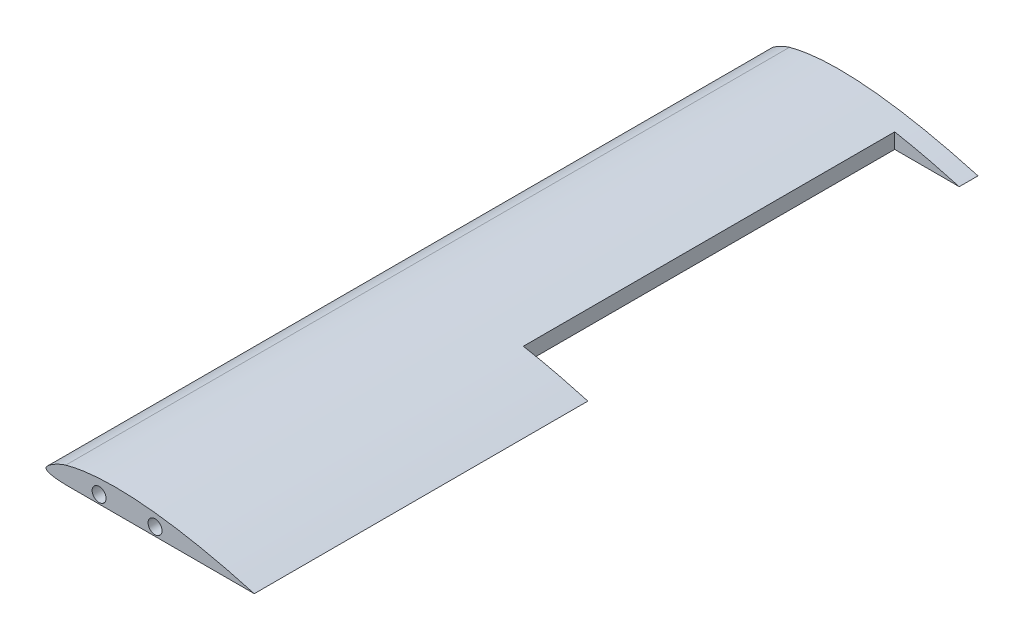
SolidWorks part; units mm, degrees
ref_plane "Спереди" through (0, 0, 0) normal (0, 0, 1) x (1, 0, 0)
ref_plane "Сверху" through (0, 0, 0) normal (0, 1, 0) x (1, 0, 0)
ref_plane "Справа" through (0, 0, 0) normal (1, 0, 0) x (0, 0, -1)
ref_plane "Плоскость4"
sketch "Эскиз1" plane through (0, 0, 0) normal (0, 0, 1) x (1, 0, 0)
  line L0 (17.2168, 0) -> (24.1571, 0)
  line L1 (24.1571, 0) -> (150, 0)
  arc A0 (14.5075, 0) -> (17.2168, 0) centre (15.8621, 58.4021) ccw
  spline S0 degree 3 poles (150, 0) (149.8103, 0.0535) (148.8822, 0.315) (147.2148, 0.7812) (144.639, 1.4911) (142.8004, 1.9884) (141.3183, 2.3846) (139.4528, 2.8811) (136.6768, 3.6046) (134.2803, 4.2119) (132.7921, 4.5848) (129.2358, 5.4697) (123.6524, 6.7978) (118.6331, 7.91) (115.6332, 8.5543) (112.827, 9.1477) (110.0153, 9.7153) (107.0035, 10.3033) (104.1852, 10.8417) (101.3616, 11.3518) (98.3391, 11.8786) (93.9391, 12.6222) (88.2743, 13.4797) (83.9782, 14.0488) (80.9402, 14.4335) (78.0977, 14.7702) (75.2508, 15.0677) (72.2039, 15.3694) (69.352, 15.6229) (66.4958, 15.8315) (63.4387, 16.0393) (60.5777, 16.1977) (57.7092, 16.3039) (56.1747, 16.3538) (54.7388, 16.3923) (53.3029, 16.4166) (51.7678, 16.4362) (50.3334, 16.4447) (48.901, 16.4378) (45.8405, 16.4119) (42.9833, 16.3304) (40.1345, 16.1761) (38.6139, 16.0899) (35.8528, 15.9017) (33.0174, 15.6301) (29.9988, 15.2873) (27.0919, 14.9079) (24.2789, 14.4406) (22.0363, 14.0235) (20.4413, 13.7077) (18.1073, 13.1883) (16.2535, 12.7297) (15.0549, 12.4095) (14.5965, 12.2828) (14.5075, 12.2582) knots 0 0 0 0 0.000556 0.002719 0.004883 0.008092 0.008092 0.00921 0.013537 0.016183 0.016183 0.017865 0.02652 0.032367 0.032367 0.035176 0.040459 0.040459 0.043831 0.04855 0.04855 0.052486 0.061142 0.064734 0.064734 0.069797 0.072826 0.072826 0.078453 0.080917 0.080917 0.087109 0.089009 0.089009 0.091436 0.093055 0.093055 0.095763 0.097101 0.097101 0.10441 0.105193 0.105193 0.10873 0.113048 0.113284 0.117362 0.121376 0.121376 0.123827 0.125981 0.128133 0.129209 0.129468 0.129468 0.129468 0.129468 weights 1 1 1 1 1 1 1 1 1 1 1 1 1 1 1 1 1 1 1 1 1 1 1 1 1 1 1 1 1 1 1 1 1 1 1 1 1 1 1 1 1 1 1 1 1 1 1 1 1 1 1 1 1 1 1
  spline S1 degree 3 poles (14.5075, 12.2582) (14.4875, 12.2539) (14.4469, 12.2452) (14.3857, 12.2317) (14.3033, 12.2124) (14.2007, 12.187) (14.0984, 12.1598) (14.0169, 12.1372) (13.9156, 12.1085) (13.8142, 12.0782) (13.6738, 12.0347) (13.5937, 12.0092) (13.4322, 11.9569) (13.1688, 11.8693) (12.8515, 11.758) (12.6365, 11.6794) (12.4766, 11.6204) (12.2124, 11.5211) (11.8995, 11.3986) (11.6912, 11.3151) (11.3758, 11.1877) (11.0662, 11.0589) (10.4923, 10.8126) (9.8722, 10.5382) (9.2664, 10.2556) (8.6563, 9.9625) (8.0494, 9.6632) (7.1849, 9.215) (6.2951, 8.728) (5.69, 8.3766) (5.1097, 8.0277) (4.8059, 7.839) (4.2552, 7.484) (3.961, 7.2872) (3.4181, 6.9072) (3.134, 6.6994) (2.867, 6.4926) (2.7317, 6.3876) (2.4714, 6.1801) (2.2146, 5.9616) (1.9568, 5.7332) (1.7055, 5.5015) (1.4693, 5.2619) (1.2404, 5.0151) (1.1297, 4.8881) (0.9692, 4.6876) (0.8658, 4.5525) (0.7667, 4.4091) (0.6734, 4.2643) (0.5863, 4.1187) (0.5127, 3.9696) (0.4782, 3.8903) (0.4444, 3.8119) (0.4121, 3.7248) (0.3665, 3.5662) (0.3494, 3.4827) (0.3409, 3.3966) (0.3364, 3.3454) (0.335, 3.2716) (0.3418, 3.1946) (0.3469, 3.1609) (0.3505, 3.1397) (0.3562, 3.1094) (0.3663, 3.0678) (0.3761, 3.0355) (0.3829, 3.0147) (0.3899, 2.9945) (0.3977, 2.9746) (0.4103, 2.9441) (0.4234, 2.9154) (0.4426, 2.8776) (0.468, 2.8312) (0.5076, 2.7683) (0.5452, 2.7172) (0.5718, 2.6831) (0.5983, 2.6499) (0.6262, 2.6176) (0.6554, 2.5856) (0.6845, 2.5542) (0.7146, 2.5239) (0.7456, 2.4939) (0.8075, 2.4351) (0.8726, 2.3799) (0.9405, 2.3266) (1.0079, 2.2745) (1.0774, 2.2253) (1.1488, 2.1774) (1.2903, 2.0836) (1.4366, 1.9991) (1.5883, 1.9193) (1.7385, 1.8412) (1.8924, 1.7693) (2.0503, 1.7009) (2.2063, 1.634) (2.3842, 1.564) (2.7066, 1.4462) (3.0273, 1.3387) (3.3557, 1.2415) (3.8219, 1.1116) (4.1806, 1.0234) (4.8168, 0.8827) (5.183, 0.8102) (5.8182, 0.6961) (6.1897, 0.636) (6.8222, 0.5426) (7.1992, 0.4922) (7.8288, 0.4155) (8.211, 0.3732) (9.1724, 0.2763) (9.9, 0.2167) (11.1959, 0.1293) (11.8686, 0.0933) (12.5509, 0.0637) (12.9578, 0.0464) (13.6317, 0.022) (14.2404, 0.0062) (14.5075, 0) knots -0.00005 -0.00005 -0.00005 -0.00005 0.00001 0.000072 0.000135 0.00026 0.000385 0.000447 0.00051 0.000696 0.000761 0.000945 0.000945 0.001263 0.001766 0.00194 0.00194 0.002271 0.002775 0.002936 0.002936 0.003783 0.003931 0.004792 0.0058 0.005921 0.006808 0.007817 0.008825 0.009834 0.009902 0.010842 0.010898 0.01185 0.011893 0.012859 0.012888 0.012888 0.013363 0.013867 0.013883 0.014381 0.014879 0.014879 0.015376 0.015376 0.015632 0.015874 0.015884 0.016136 0.016371 0.016371 0.016388 0.01662 0.01664 0.016869 0.016869 0.016892 0.017019 0.017082 0.017118 0.017118 0.017144 0.017207 0.017242 0.017242 0.017271 0.017304 0.017304 0.017367 0.017397 0.017429 0.017522 0.017615 0.017615 0.017649 0.01774 0.01774 0.017775 0.017864 0.017864 0.017901 0.018113 0.018113 0.018153 0.018362 0.018362 0.018405 0.01886 0.01886 0.018909 0.019357 0.019357 0.019414 0.019855 0.019918 0.020422 0.02085 0.020926 0.021845 0.021935 0.022841 0.022943 0.023836 0.023951 0.024831 0.02496 0.025826 0.025968 0.027817 0.027985 0.029807 0.029807 0.030002 0.03101 0.031798 0.031798 0.031798 0.031798 weights 1 1 1 1 1 1 1 1 1 1 1 1 1 1 1 1 1 1 1 1 1 1 1 1 1 1 1 1 1 1 1 1 1 1 1 1 1 1 1 1 1 1 1 1 1 1 1 1 1 1 1 1 1 1 1 1 1 1 1 1 1 1 1 1 1 1 1 1 1 1 1 1 1 1 1 1 1 1 1 1 1 1 1 1 1 1 1 1 1 1 1 1 1 1 1 1 1 1 1 1 1 1 1 1 1 1 1 1 1 1 1 1 1 1 1 1 1
extrude "Выдавливание1" add sketch "Эскиз1" along normal blind 520
ref_plane "Плоскость5"
sketch "Эскиз2" plane through (0, 0, 520) normal (0, 0, 1) x (1, 0, 0)
  circle A0 centre (78.7009, 6) radius 5
  circle A1 centre (38.5008, 6) radius 5
  dimension "D1" = 10
extrude "Выдавливание2" cut sketch "Эскиз2" against normal blind 200 contours A0 | A1
sketch "Эскиз3" plane through (0, 0, 0) normal (0, -1, 0) x (1, 0, 0)
  line L0 (128.3183, 305) -> (128.3183, 330)
  line L1 (128.3183, 330) -> (28.3183, 330)
  line L2 (28.3183, 330) -> (28.3183, 305)
  line L3 (28.3183, 305) -> (128.3183, 305)
  dimension "D1" = 25
  dimension "D2" = 100
extrude "Выдавливание3" add sketch "Эскиз3" along normal blind 35
sketch "Эскиз4" plane through (128.3183, 0, 0) normal (1, 0, 0) x (0, 0, -1)
  line L0 (-327.5, -25) -> (-327.5, -35)
  line L1 (-327.5, -35) -> (-307.5, -35)
  line L2 (-307.5, -35) -> (-307.5, -25)
  line L3 (-307.5, -25) -> (-307.5, -15)
  line L4 (-327.5, -15) -> (-327.5, -25)
  arc A0 (-307.5, -15) -> (-327.5, -15) centre (-317.5, -15) ccw
  dimension "D1" = 10
extrude "Выдавливание5" cut sketch "Эскиз4" against normal through all
sketch "Эскиз5" plane through (0, 0, 330) normal (0, 0, 1) x (1, 0, 0)
  circle A0 centre (98.3183, -25) radius 5
  circle A1 centre (78.3183, -25) radius 5
  circle A2 centre (58.3183, -25) radius 5
  line M1 (128.3183, 0) -> (28.3183, 0)
  line M2 (28.3183, 0) -> (28.3183, -35)
  line M3 (28.3183, -35) -> (128.3183, -35)
  line M4 (128.3183, -35) -> (128.3183, 0)
  dimension "D1" = 10
  dimension "D2" = 10
  dimension "D3" = 10
extrude "Выдавливание6" cut sketch "Эскиз5" against normal through all contours A2 A1 A0 M4 M1 M2 M3
sketch "Эскиз6" plane through (0, 0, 0) normal (0, -1, 0) x (1, 0, 0)
  line L0 (101.6272, 11.4767) -> (103.6272, 11.4767)
  line L1 (103.6272, 11.4767) -> (163.8005, 11.4767)
  line L2 (163.8005, 11.4767) -> (163.8005, 282.2938)
  line L3 (163.8005, 282.2938) -> (161.8005, 282.2938)
  line L4 (161.8005, 282.2938) -> (101.6272, 282.2938)
  line L5 (101.6272, 282.2938) -> (101.6272, 11.4767)
  line L6 (161.8005, 13.4767) -> (103.6272, 13.4767)
  line L7 (103.6272, 13.4767) -> (103.6272, 280.2938)
  line L8 (103.6272, 280.2938) -> (161.8005, 280.2938)
  line L9 (161.8005, 280.2938) -> (161.8005, 13.4767)
  line M2 (150, 0) -> (150, 520)
  dimension "D1" = 2
  dimension "D2" = 2
  dimension "D3" = 2
  dimension "D4" = 2
extrude "Выдавливание7" cut sketch "Эскиз6" against normal through all contours L8 L7 L6 M2
sketch "Эскиз7" plane through (0, 0, 0) normal (0, -1, 0) x (1, 0, 0)
  line L0 (103.6272, 25.8852) -> (103.6272, 27.8852)
  line L1 (103.6272, 27.8852) -> (101.6272, 27.8852)
  line L2 (101.6272, 27.8852) -> (101.6272, 25.8852)
  line L3 (101.6272, 25.8852) -> (103.6272, 25.8852)
  line L4 (103.6272, 45.8852) -> (103.6272, 47.8852)
  line L5 (103.6272, 47.8852) -> (101.6272, 47.8852)
  line L6 (101.6272, 47.8852) -> (101.6272, 45.8852)
  line L7 (101.6272, 45.8852) -> (103.6272, 45.8852)
  line L8 (103.6272, 35.8852) -> (103.6272, 37.8852)
  line L9 (103.6272, 37.8852) -> (101.6272, 37.8852)
  line L10 (101.6272, 37.8852) -> (101.6272, 35.8852)
  line L11 (101.6272, 35.8852) -> (103.6272, 35.8852)
  line L12 (103.6272, 55.8852) -> (103.6272, 57.8852)
  line L13 (103.6272, 57.8852) -> (101.6272, 57.8852)
  line L14 (101.6272, 57.8852) -> (101.6272, 55.8852)
  line L15 (101.6272, 55.8852) -> (103.6272, 55.8852)
  line L16 (103.6272, 65.8852) -> (103.6272, 67.8852)
  line L17 (103.6272, 67.8852) -> (101.6272, 67.8852)
  line L18 (101.6272, 67.8852) -> (101.6272, 65.8852)
  line L19 (101.6272, 65.8852) -> (103.6272, 65.8852)
  line L20 (103.6272, 75.8852) -> (103.6272, 77.8852)
  line L21 (103.6272, 77.8852) -> (101.6272, 77.8852)
  line L22 (101.6272, 77.8852) -> (101.6272, 75.8852)
  line L23 (101.6272, 75.8852) -> (103.6272, 75.8852)
  line L24 (103.6272, 85.8852) -> (103.6272, 87.8852)
  line L25 (103.6272, 87.8852) -> (101.6272, 87.8852)
  line L26 (101.6272, 87.8852) -> (101.6272, 85.8852)
  line L27 (101.6272, 85.8852) -> (103.6272, 85.8852)
  line L28 (103.6272, 95.8852) -> (103.6272, 97.8852)
  line L29 (103.6272, 97.8852) -> (101.6272, 97.8852)
  line L30 (101.6272, 97.8852) -> (101.6272, 95.8852)
  line L31 (101.6272, 95.8852) -> (103.6272, 95.8852)
  line L32 (103.6272, 105.8852) -> (103.6272, 107.8852)
  line L33 (103.6272, 107.8852) -> (101.6272, 107.8852)
  line L34 (101.6272, 107.8852) -> (101.6272, 105.8852)
  line L35 (101.6272, 105.8852) -> (103.6272, 105.8852)
  line L36 (103.6272, 115.8852) -> (103.6272, 117.8852)
  line L37 (103.6272, 117.8852) -> (101.6272, 117.8852)
  line L38 (101.6272, 117.8852) -> (101.6272, 115.8852)
  line L39 (101.6272, 115.8852) -> (103.6272, 115.8852)
  line L40 (103.6272, 125.8852) -> (103.6272, 127.8852)
  line L41 (103.6272, 127.8852) -> (101.6272, 127.8852)
  line L42 (101.6272, 127.8852) -> (101.6272, 125.8852)
  line L43 (101.6272, 125.8852) -> (103.6272, 125.8852)
  line L44 (103.6272, 145.8852) -> (103.6272, 147.8852)
  line L45 (103.6272, 147.8852) -> (101.6272, 147.8852)
  line L46 (101.6272, 147.8852) -> (101.6272, 145.8852)
  line L47 (101.6272, 145.8852) -> (103.6272, 145.8852)
  line L48 (103.6272, 135.8852) -> (103.6272, 137.8852)
  line L49 (103.6272, 137.8852) -> (101.6272, 137.8852)
  line L50 (101.6272, 137.8852) -> (101.6272, 135.8852)
  line L51 (101.6272, 135.8852) -> (103.6272, 135.8852)
  line L52 (103.6272, 155.8852) -> (103.6272, 157.8852)
  line L53 (103.6272, 157.8852) -> (101.6272, 157.8852)
  line L54 (101.6272, 157.8852) -> (101.6272, 155.8852)
  line L55 (101.6272, 155.8852) -> (103.6272, 155.8852)
  line L56 (103.6272, 165.8852) -> (103.6272, 167.8852)
  line L57 (103.6272, 167.8852) -> (101.6272, 167.8852)
  line L58 (101.6272, 167.8852) -> (101.6272, 165.8852)
  line L59 (101.6272, 165.8852) -> (103.6272, 165.8852)
  line L60 (103.6272, 175.8852) -> (103.6272, 177.8852)
  line L61 (103.6272, 177.8852) -> (101.6272, 177.8852)
  line L62 (101.6272, 177.8852) -> (101.6272, 175.8852)
  line L63 (101.6272, 175.8852) -> (103.6272, 175.8852)
  line L64 (103.6272, 185.8852) -> (103.6272, 187.8852)
  line L65 (103.6272, 187.8852) -> (101.6272, 187.8852)
  line L66 (101.6272, 187.8852) -> (101.6272, 185.8852)
  line L67 (101.6272, 185.8852) -> (103.6272, 185.8852)
  line L68 (103.6272, 195.8852) -> (103.6272, 197.8852)
  line L69 (103.6272, 197.8852) -> (101.6272, 197.8852)
  line L70 (101.6272, 197.8852) -> (101.6272, 195.8852)
  line L71 (101.6272, 195.8852) -> (103.6272, 195.8852)
  line L72 (103.6272, 205.8852) -> (103.6272, 207.8852)
  line L73 (103.6272, 207.8852) -> (101.6272, 207.8852)
  line L74 (101.6272, 207.8852) -> (101.6272, 205.8852)
  line L75 (101.6272, 205.8852) -> (103.6272, 205.8852)
  line L76 (103.6272, 215.8852) -> (103.6272, 217.8852)
  line L77 (103.6272, 217.8852) -> (101.6272, 217.8852)
  line L78 (101.6272, 217.8852) -> (101.6272, 215.8852)
  line L79 (101.6272, 215.8852) -> (103.6272, 215.8852)
  line L80 (103.6272, 225.8852) -> (103.6272, 227.8852)
  line L81 (103.6272, 227.8852) -> (101.6272, 227.8852)
  line L82 (101.6272, 227.8852) -> (101.6272, 225.8852)
  line L83 (101.6272, 225.8852) -> (103.6272, 225.8852)
  line L84 (103.6272, 235.8852) -> (103.6272, 237.8852)
  line L85 (103.6272, 237.8852) -> (101.6272, 237.8852)
  line L86 (101.6272, 237.8852) -> (101.6272, 235.8852)
  line L87 (101.6272, 235.8852) -> (103.6272, 235.8852)
  line L88 (103.6272, 245.8852) -> (103.6272, 247.8852)
  line L89 (103.6272, 247.8852) -> (101.6272, 247.8852)
  line L90 (101.6272, 247.8852) -> (101.6272, 245.8852)
  line L91 (101.6272, 245.8852) -> (103.6272, 245.8852)
  line L92 (103.6272, 255.8852) -> (103.6272, 257.8852)
  line L93 (103.6272, 257.8852) -> (101.6272, 257.8852)
  line L94 (101.6272, 257.8852) -> (101.6272, 255.8852)
  line L95 (101.6272, 255.8852) -> (103.6272, 255.8852)
  line L96 (103.6272, 265.8852) -> (103.6272, 267.8852)
  line L97 (103.6272, 267.8852) -> (101.6272, 267.8852)
  line L98 (101.6272, 267.8852) -> (101.6272, 265.8852)
  line L99 (101.6272, 265.8852) -> (103.6272, 265.8852)
  dimension "D1" = 2
extrude "Выдавливание8" add sketch "Эскиз7" against normal blind 8
